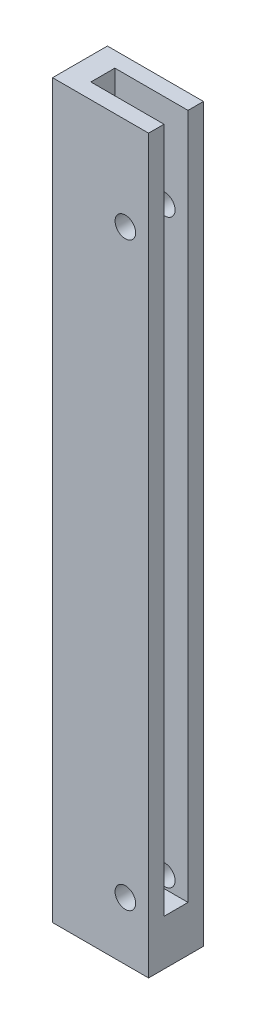
SolidWorks part; units mm, degrees
material "ABS"
ref_plane "Front Plane" through (0, 0, 0) normal (0, 0, 1) x (1, 0, 0)
ref_plane "Top Plane" through (0, 0, 0) normal (0, 1, 0) x (1, 0, 0)
ref_plane "Right Plane" through (0, 0, 0) normal (1, 0, 0) x (0, 0, -1)
sketch "Sketch1" plane through (0, 0, 0) normal (0, 0, 1) x (1, 0, 0)
  line L0 (15.92, 160) -> (15.92, 0) construction
  line L1 (0, 0) -> (21, 0)
  line L2 (0, 0) -> (0, 160)
  line L3 (0, 160) -> (21, 160)
  line L4 (21, 0) -> (21, 160)
  circle A0 centre (15.92, 12.7) radius 2.2479
  circle A1 centre (15.92, 139.7) radius 2.2479
  point P11 (0, 0)
  point P12 (0, 0)
  dimension "D5" = 4.4958
  dimension "D1" = 21
  dimension "D2" = 160
  dimension "D3" = 127
  dimension "D4" = 12.7
  dimension "D6" = 5.08
extrude "Boss-Extrude1" add sketch "Sketch1" along normal blind 12
sketch "Sketch2" plane through (21, 0, 0) normal (1, 0, 0) x (0, 0, -1)
  line L0 (-12, 160) -> (0, 160) construction
  line L1 (-8.625, 10) -> (-3.375, 10)
  line L2 (-8.625, 10) -> (-8.625, 160)
  line L3 (-8.625, 160) -> (-3.375, 160)
  line L4 (-3.375, 10) -> (-3.375, 160)
  point P6 (-6, 160)
  point P7 (-6, 160)
  dimension "D1" = 150
  dimension "D2" = 5.25
extrude "Cut-Extrude1" cut sketch "Sketch2" against normal blind 16
sketch "Sketch3" plane through (0, 0, 12) normal (0, 0, 1) x (1, 0, 0)
